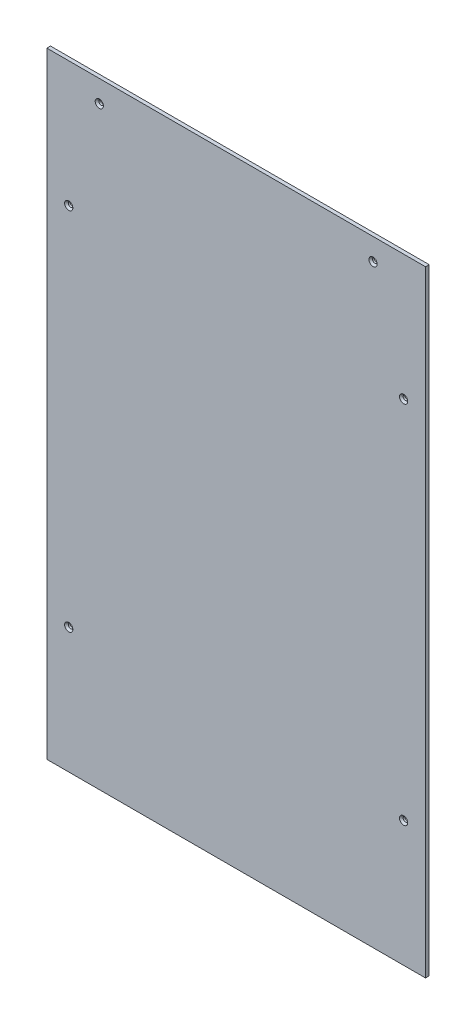
SolidWorks part; units mm, degrees
material "1.4301 (X5CrNi18-10)"
ref_plane "Plan de face" through (0, 0, 0) normal (0, 0, 1) x (1, 0, 0)
ref_plane "Plan de dessus" through (0, 0, 0) normal (0, 1, 0) x (1, 0, 0)
ref_plane "Plan de droite" through (0, 0, 0) normal (1, 0, 0) x (0, 0, -1)
sketch "Esquisse1" plane through (0, 0, 0) normal (0, 0, 1) x (1, 0, 0)
  line L1 (-207.5, -337.5) -> (207.5, -337.5)
  line L2 (-207.5, -337.5) -> (-207.5, 337.5)
  line L3 (-207.5, 337.5) -> (207.5, 337.5)
  line L4 (207.5, -337.5) -> (207.5, 337.5)
  line L5 (-207.5, -337.5) -> (207.5, 337.5) construction
  line L6 (-207.5, 337.5) -> (207.5, -337.5) construction
  point P0 (0, 0)
  dimension "D1" = 675
  dimension "D2" = 415
extrude "Boss.-Extru.1" add sketch "Esquisse1" along normal mid plane 4
sketch "Esquisse2" plane through (0, 0, 2) normal (0, 0, 1) x (1, 0, 0)
  line L0 (207.5, 337.5) -> (-207.5, 337.5) construction
  line L1 (-183.5, -313.5) -> (183.5, -313.5) construction
  line L2 (-183.5, -313.5) -> (-183.5, 313.5) construction
  line L3 (-183.5, 313.5) -> (183.5, 313.5) construction
  line L4 (183.5, -313.5) -> (183.5, 313.5) construction
  line L5 (-183.5, -313.5) -> (183.5, 313.5) construction
  line L6 (-183.5, 313.5) -> (183.5, -313.5) construction
  line L7 (207.5, -337.5) -> (207.5, 337.5) construction
  line L8 (183.5, 0) -> (-183.5, 0) construction
  line L9 (0, 313.5) -> (0, -313.5) construction
  circle A0 centre (183.5, 200) radius 2.5
  circle A1 centre (183.5, -200) radius 2.5
  circle A2 centre (150, 313.5) radius 2.5
  circle A3 centre (-150, 313.5) radius 2.5
  circle A4 centre (-183.5, 200) radius 2.5
  circle A5 centre (-183.5, -200) radius 2.5
  point P0 (0, 0)
  dimension "D3" = 5
  dimension "D1" = 24
  dimension "D2" = 24
  dimension "D4" = 300
  dimension "D5" = 400
extrude "Enlèv. mat.-Extru.1" cut sketch "Esquisse2" against normal through all
chamfer "Chanfrein1" distance 2 angle 45 6 edges at (-181, 200, 2) (-181, -200, 2) (186, -200, 2) (186, 200, 2) (152.5, 313.5, 2) (-147.5, 313.5, 2)
